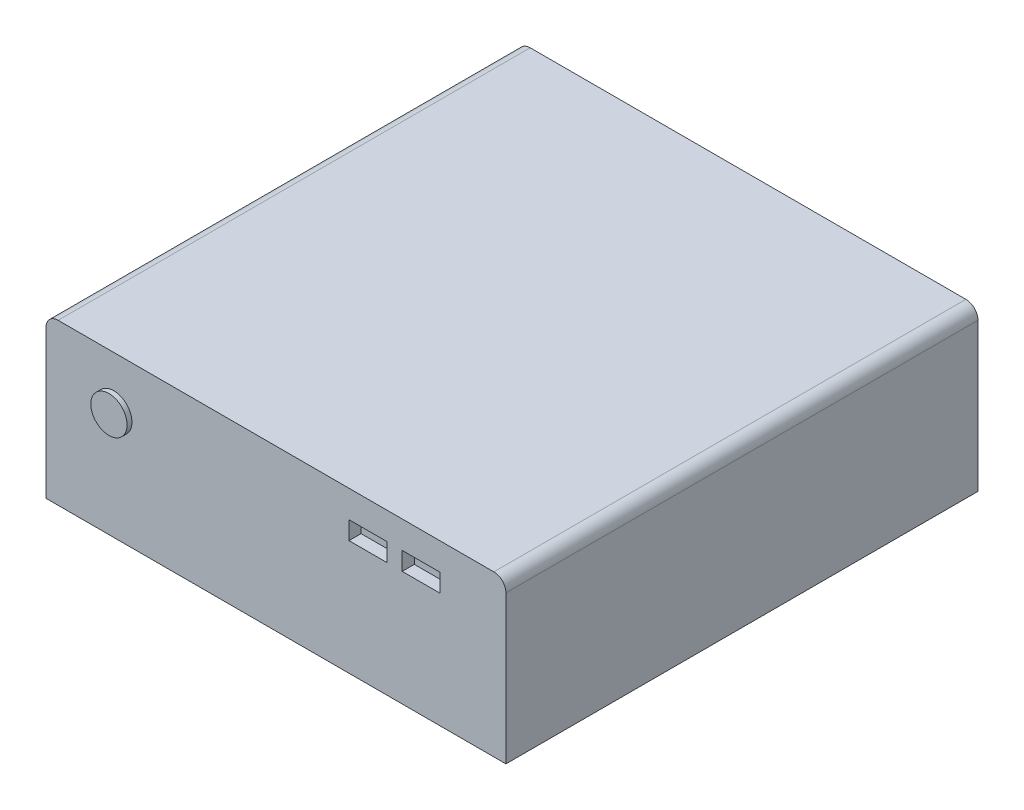
SolidWorks part; units mm, degrees
ref_plane "Front Plane" through (0, 0, 0) normal (0, 0, 1) x (1, 0, 0)
ref_plane "Top Plane" through (0, 0, 0) normal (0, 1, 0) x (1, 0, 0)
ref_plane "Right Plane" through (0, 0, 0) normal (1, 0, 0) x (0, 0, -1)
sketch "Sketch1" plane through (0, 0, 0) normal (0, 1, 0) x (1, 0, 0)
  line L1 (-95, 97.5) -> (95, 97.5)
  line L2 (-95, 97.5) -> (-95, -97.5)
  line L3 (-95, -97.5) -> (95, -97.5)
  line L4 (95, 97.5) -> (95, -97.5)
  line L5 (-95, 97.5) -> (95, -97.5) construction
  line L6 (-95, -97.5) -> (95, 97.5) construction
  point P0 (0, 0)
  dimension "D1" = 190
  dimension "D2" = 195
extrude "Boss-Extrude1" add sketch "Sketch1" along normal blind 66.2
fillet "Fillet1" radius 5 2 edges at (95, 66.2, 0) (-95, 66.2, 0)
sketch "Sketch2" plane through (0, 0, 0) normal (0, -1, 0) x (-1, 0, 0)
  line L1 (85.725, 45) -> (-85.725, 45) construction
  line L2 (85.725, 45) -> (85.725, -45) construction
  line L3 (85.725, -45) -> (-85.725, -45) construction
  line L4 (-85.725, 45) -> (-85.725, -45) construction
  line L5 (85.725, 45) -> (-85.725, -45) construction
  line L6 (85.725, -45) -> (-85.725, 45) construction
  circle A0 centre (85.725, -45) radius 1.7
  circle A1 centre (-85.725, -45) radius 1.7
  circle A2 centre (-85.725, 45) radius 1.7
  circle A3 centre (85.725, 45) radius 1.7
  point P0 (0, 0)
  dimension "D1" = 3.4
  dimension "D2" = 90
  dimension "D3" = 171.45
extrude "Cut-Extrude1" cut sketch "Sketch2" against normal blind 5
sketch "Sketch3" plane through (0, 0, 97.5) normal (0, 0, 1) x (1, 0, 0)
  line L0 (-95, 0) -> (95, 0) construction
  line L1 (-95, 61.2) -> (-95, 0) construction
  circle A0 centre (-67, 45) radius 7.5
  dimension "D3" = 15
  dimension "D1" = 45
  dimension "D2" = 28
extrude "Boss-Extrude2" add sketch "Sketch3" along normal blind 2
sketch "Sketch4" plane through (0, 0, 97.5) normal (0, 0, 1) x (1, 0, 0)
  line L0 (95, 51.2) -> (60, 51.2) construction
  line L1 (95, 61.2) -> (95, 0) construction
  line L2 (60, 51.2) -> (38, 51.2) construction
  line L3 (-90, 66.2) -> (90, 66.2) construction
  line L4 (45.85, 47.45) -> (30.15, 47.45)
  line L5 (45.85, 47.45) -> (45.85, 54.95)
  line L6 (45.85, 54.95) -> (30.15, 54.95)
  line L7 (30.15, 47.45) -> (30.15, 54.95)
  line L8 (45.85, 47.45) -> (30.15, 54.95) construction
  line L9 (45.85, 54.95) -> (30.15, 47.45) construction
  line L10 (67.85, 47.45) -> (52.15, 47.45)
  line L11 (67.85, 47.45) -> (67.85, 54.95)
  line L12 (67.85, 54.95) -> (52.15, 54.95)
  line L13 (52.15, 47.45) -> (52.15, 54.95)
  line L14 (67.85, 47.45) -> (52.15, 54.95) construction
  line L15 (67.85, 54.95) -> (52.15, 47.45) construction
  dimension "D1" = 15.7
  dimension "D2" = 7.5
  dimension "D3" = 35
  dimension "D4" = 15
  dimension "D5" = 22
extrude "Cut-Extrude2" cut sketch "Sketch4" against normal blind 5
